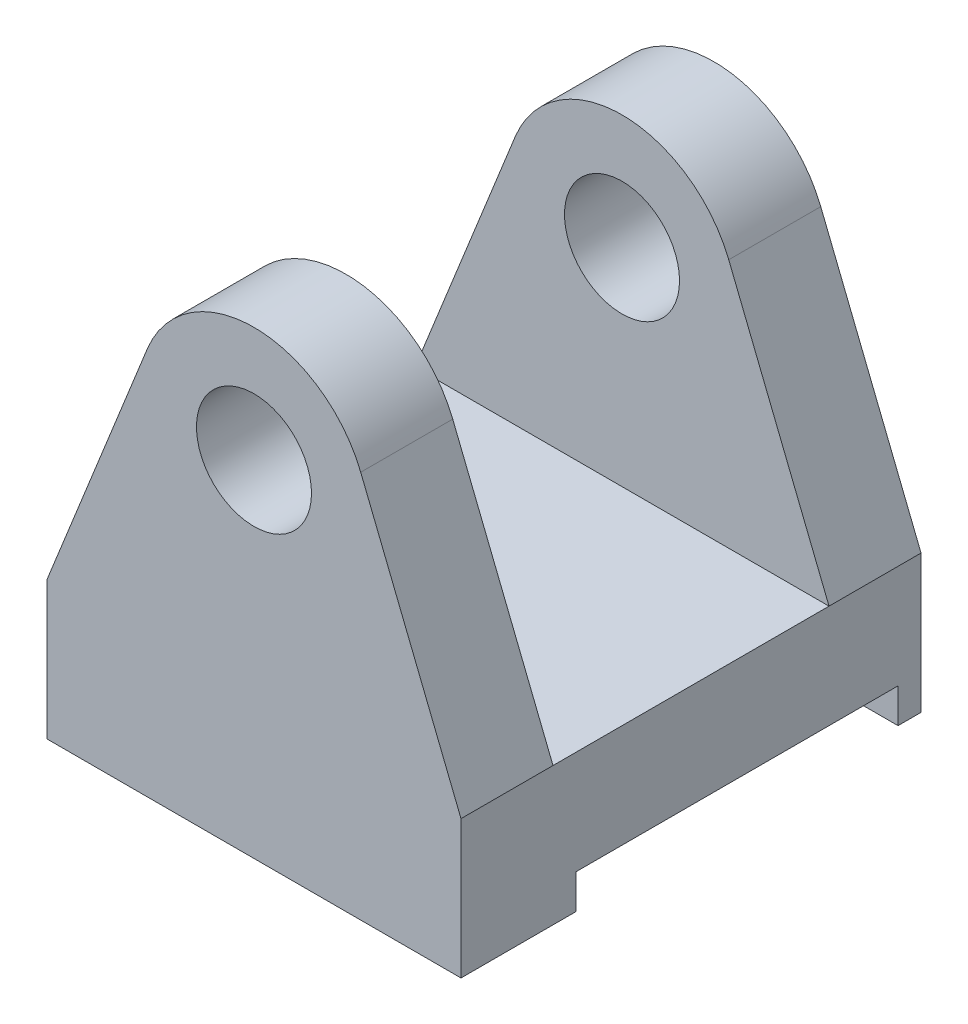
SolidWorks part; units mm, degrees
ref_plane "前视基准面" through (0, 0, 0) normal (0, 0, 1) x (1, 0, 0)
ref_plane "上视基准面" through (0, 0, 0) normal (0, 1, 0) x (1, 0, 0)
ref_plane "右视基准面" through (0, 0, 0) normal (1, 0, 0) x (0, 0, -1)
sketch "草图1" plane through (0, 0, 0) normal (0, 0, 1) x (1, 0, 0)
  line L0 (4.6402, 13.8624) -> (9, 3)
  line L1 (-9, 3) -> (9, 3)
  line L2 (-9, 3) -> (-9, -3)
  line L3 (-9, -3) -> (9, -3)
  line L4 (9, 3) -> (9, -3)
  line L5 (-9, 3) -> (9, -3) construction
  line L6 (-9, -3) -> (9, 3) construction
  line L7 (-9, 3) -> (-4.6402, 13.8624)
  circle A0 centre (0, 12) radius 5
  point P0 (0, 0)
  point P9 (0, 0)
  dimension "D1" = 6
  dimension "D2" = 15
  dimension "D3" = 10
  dimension "D4" = 18
extrude "凸台-拉伸1" add sketch "草图1" along normal mid plane 20 contours A0 | A0 L7 L1 L0 | L4 L1 L2 L3
sketch "草图2" plane through (9, 0, 0) normal (1, 0, 0) x (0, 0, -1)
  line L0 (-10, -3) -> (10, -3) construction
  line L1 (-5, -1.5) -> (9, -1.5)
  line L2 (-5, -1.5) -> (-5, -4.5)
  line L3 (-5, -4.5) -> (9, -4.5)
  line L4 (9, -1.5) -> (9, -4.5)
  line L5 (-5, -1.5) -> (9, -4.5) construction
  line L6 (-5, -4.5) -> (9, -1.5) construction
  line L7 (10, 3) -> (10, -3) construction
  point P0 (2, -3)
  point P7 (0, 0)
  point P10 (8, -4.5844)
  point P11 (0, 0)
  dimension "D1" = 1.5
  dimension "D2" = 14
  dimension "D3" = 1
extrude "切除-拉伸1" cut sketch "草图2" against normal through all both and the other way through all
sketch "草图3" plane through (0, 0, 10) normal (0, 0, 1) x (1, 0, 0)
  line L0 (-9, 3) -> (9, 3)
  line L5 (-4.6402, 13.8624) -> (-9, 3)
  line L6 (-9, 3) -> (-9, -3)
  line L7 (-9, -3) -> (9, -3)
  line L8 (9, -3) -> (9, 3)
  line L9 (9, 3) -> (4.6402, 13.8624)
  line L10 (-4.6402, 13.8624) -> (-9, 3)
  line L11 (-9, 3) -> (-9, -3)
  line L12 (-9, -3) -> (9, -3)
  line L13 (9, -3) -> (9, 3)
  line L14 (9, 3) -> (4.6402, 13.8624)
  arc A1 (4.6402, 13.8624) -> (-4.6402, 13.8624) centre (0, 12) ccw
  arc A2 (4.6402, 13.8624) -> (-4.6402, 13.8624) centre (0, 12) ccw
  arc M7 (4.6402, 13.8624) -> (-4.6402, 13.8624) centre (0, 12) ccw
  line M8 (-4.6402, 13.8624) -> (-9, 3)
  line M12 (9, 3) -> (4.6402, 13.8624)
  dimension "D1" = 0
extrude "切除-拉伸2" cut sketch "草图3" against normal blind 12 from offset 4 contours L0 M8 M12 M7 offset against normal yes
sketch "草图4" plane through (0, 0, 10) normal (0, 0, 1) x (1, 0, 0)
  circle A0 centre (0, 12) radius 2.5
  arc A1 (4.6402, 13.8624) -> (-4.6402, 13.8624) centre (0, 12) ccw construction
  dimension "D1" = 5
extrude "切除-拉伸3" cut sketch "草图4" against normal through all both and the other way through all
